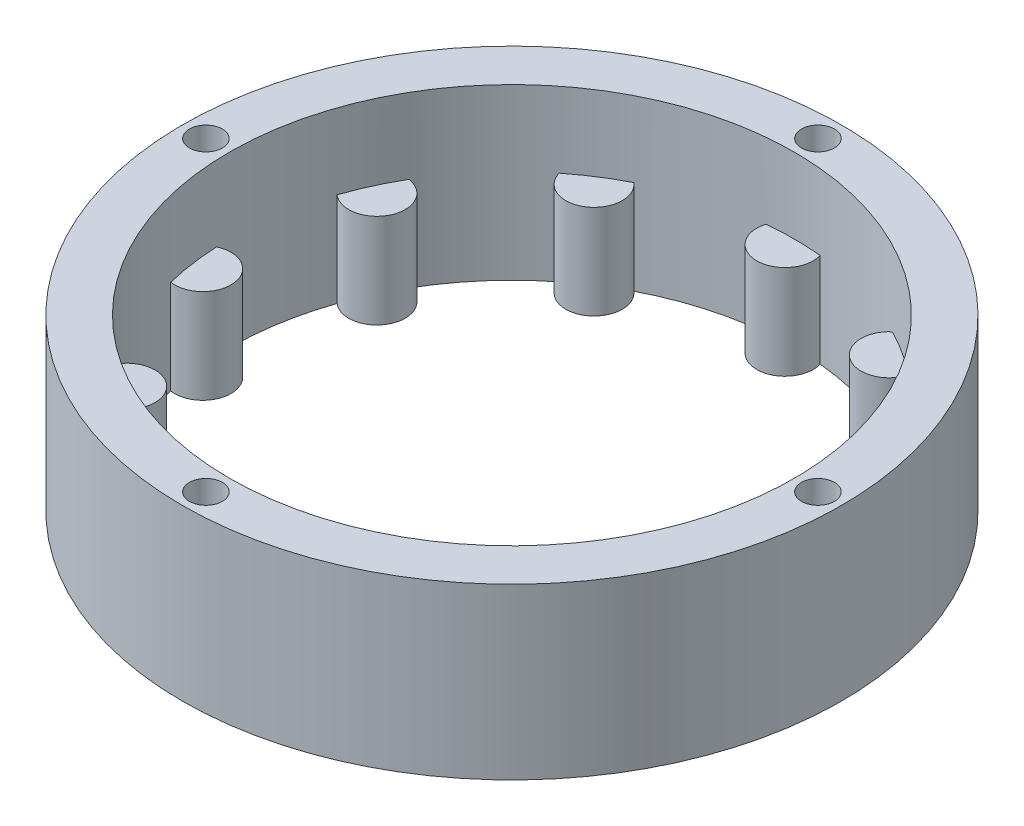
SolidWorks part; units mm, degrees
ref_plane "Front Plane" through (0, 0, 0) normal (0, 0, 1) x (1, 0, 0)
ref_plane "Top Plane" through (0, 0, 0) normal (0, 1, 0) x (1, 0, 0)
ref_plane "Right Plane" through (0, 0, 0) normal (1, 0, 0) x (0, 0, -1)
sketch "Sketch1" plane through (0, 0, 0) normal (0, 1, 0) x (1, 0, 0)
  line L0 (0, 0) -> (-41614.7945, 0) construction
  line L1 (0, 0) -> (0, -41614.7945) construction
  circle A0 centre (0, 0) radius 35
  circle A1 centre (0, 0) radius 30
  dimension "D1" = 70
  dimension "D2" = 60
extrude "Boss-Extrude1" add sketch "Sketch1" along normal blind 18
sketch "Sketch2" plane through (0, 0, 0) normal (0, 1, 0) x (1, 0, 0)
  line L0 (0, 0) -> (-50000, 0) construction
  line L1 (0, 0) -> (0, -50000) construction
  circle A0 centre (0, 0) radius 29 construction
  circle A2 centre (0, 29) radius 3
  circle A3 centre (15.6786, 24.3964) radius 3
  circle A4 centre (26.3793, 12.047) radius 3
  circle A5 centre (28.7048, -4.1271) radius 3
  circle A6 centre (21.9167, -18.991) radius 3
  circle A7 centre (8.1702, -27.8253) radius 3
  circle A8 centre (-8.1702, -27.8253) radius 3
  circle A9 centre (-21.9167, -18.991) radius 3
  circle A10 centre (-28.7048, -4.1271) radius 3
  circle A11 centre (-26.3793, 12.047) radius 3
  circle A12 centre (-15.6786, 24.3964) radius 3
  point P32 (0, 0)
  dimension "D1" = 58
  dimension "D2" = 6
extrude "Boss-Extrude2" add sketch "Sketch2" along normal blind 10
sketch "Sketch3" plane through (0, 18, 0) normal (0, 1, 0) x (1, 0, 0)
  line L0 (0, 0) -> (-50000, 0) construction
  line L1 (0, 0) -> (0, -50000) construction
  circle A0 centre (0, 0) radius 32.5 construction
  circle A1 centre (0, 32.5) radius 1.75
  circle A2 centre (32.5, 0) radius 1.75
  circle A3 centre (0, -32.5) radius 1.75
  circle A4 centre (-32.5, 0) radius 1.75
  point P18 (0, 0)
  dimension "D1" = 65
  dimension "D2" = 3.5
extrude "Cut-Extrude1" cut sketch "Sketch3" against normal through all
